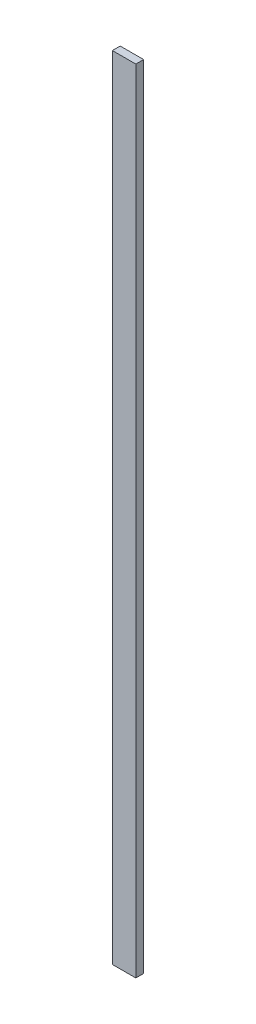
SolidWorks part; units mm, degrees
ref_plane "Спереди" through (0, 0, 0) normal (0, 0, 1) x (1, 0, 0)
ref_plane "Сверху" through (0, 0, 0) normal (0, 1, 0) x (1, 0, 0)
ref_plane "Справа" through (0, 0, 0) normal (1, 0, 0) x (0, 0, -1)
sketch "Эскиз1" plane through (0, 0, 0) normal (0, 0, 1) x (1, 0, 0)
  line L1 (-455, 506.285) -> (-425, 506.285)
  line L2 (-455, 506.285) -> (-455, -506.285)
  line L3 (-455, -506.285) -> (-425, -506.285)
  line L4 (-425, 506.285) -> (-425, -506.285)
  point P4 (-455, 506.285)
  point P5 (-425, -506.285)
extrude "Бобышка-Вытянуть1" add sketch "Эскиз1" against normal blind 10
equation "\"Ширина груза\"= 420"
equation "\"Глубина груза\"= 490"
equation "\"Высота груза\"= 297"
equation "\"Ширина ячейки\"= \"Ширина груза\" + 10"
equation "\"Глубина ячейки\"= \"Глубина груза\" + 10"
equation "\"Высота ячейки\"= \"Высота груза\" + 10 + 13"
equation "\"Колво ячеек ширина\"= 2"
equation "\"Колво ячеек высота\"= 2"
equation "\"Толщина стенки\"= 10"
equation "\"Крепление дверцы\"= 5"
equation "\"Ширина рейки\"= \"Толщина шестерни\""
equation "\"Высота рейки\"= 20"
equation "\"Высота пола\"= 20"
equation "\"Колво полозьев\"= 5"
equation "\"Отступ рейки\"= 20"
equation "\"Глубина каретки\"= \"Глубина ячейки\" + 30 + \"Мотор Y высота корпуса\" + 20"
equation "\"Длинна рейки\"= ( \"Ширина ячейки\" + \"Толщина стенки\" + \"Крепление дверцы\" ) * \"Колво ячеек ширина\" + \"Ширина ячейки выгрузки\" * \"Колво выгрузки\" + \"Толщина стенки\""
equation "\"Отступ шпильки\"= 26"
equation "\"Диаметр шпильки\"= 5"
equation "\"Длинна шпильки\"= ( \"Высота ячейки\" + \"Толщина стенки\" + \"Высота пола\" ) * \"Колво ячеек высота\" + ( \"Толщина стенки\" + \"Отступ рейки\" ) * 2 "
equation "\"Ширина пластины\"= 50  "
equation "\"Высота зона выгрузки\"= \"Высота ячейки\" * 2 + \"Толщина стенки\" * 2"
equation "\"Колво выгрузки\"= 1"
equation "\"Ширина ячейки выгрузки\"= \"Ширина ячейки\" + \"Толщина стенки\" + \"Отступ крепления мотора фиксации\"*2"
equation "\"Отступ крепления мотора фиксации\" = 30"
equation "\"Мотор X ширина корпуса\"= 42.3"
equation "\"Мотор X высота корпуса\"= 42.3"
equation "\"Мотор X длина корпуса\"= 40"
equation "\"Мотор X вылет вала\"= 19.8"
equation "\"Мотор Y ширина корпуса\"= 42.3"
equation "\"Мотор Y высота корпуса\"= 42.3"
equation "\"Мотор Y длина корпуса\"= 48"
equation "\"Мотор Y вылет вала\"= 30"
equation "\"Мотор Z ширина корпуса\"= 42"
equation "\"Мотор Z высота корпуса\"= 42"
equation "\"Мотор Z длина корпуса\"= 40"
equation "\"Мотор Z вылет вала\"= 23"
equation "\"Мотор диаметр вала ПРЕДВ\"= 5"
equation "\"Мотор шаг крепления ПРЕДВ\"= 31"
equation "\"Мотор диаметр отверстий ПРЕДВ\"= 3"
equation "\"Мотор глубина отверстий ПРЕДВ\"= 4.5"
equation "\"Мотор диаметр буртика ПРЕДВ\"= 22"
equation "\"Мотор высота буртика ПРЕДВ\"= 2"
equation "\"Мотор диаметр шкива ПРЕДВ\"= 16"
equation "\"Мотор длина шкива ПРЕДВ\"= 12"
equation "\"Мотор отступ шкива ПРЕДВ\"= 5"
equation "\"Мотор X шаг градусов\"= 1.8"
equation "\"Мотор Y шаг градусов\"= 1.8"
equation "\"Мотор Z шаг градусов\"= 1.8"
equation "\"Мотор Y диаметр ротора\"= 25.78"
equation "\"Толщина шестерни\"= 10"
equation "\"D1@Бобышка-Вытянуть1\"=\"Толщина стенки\""
